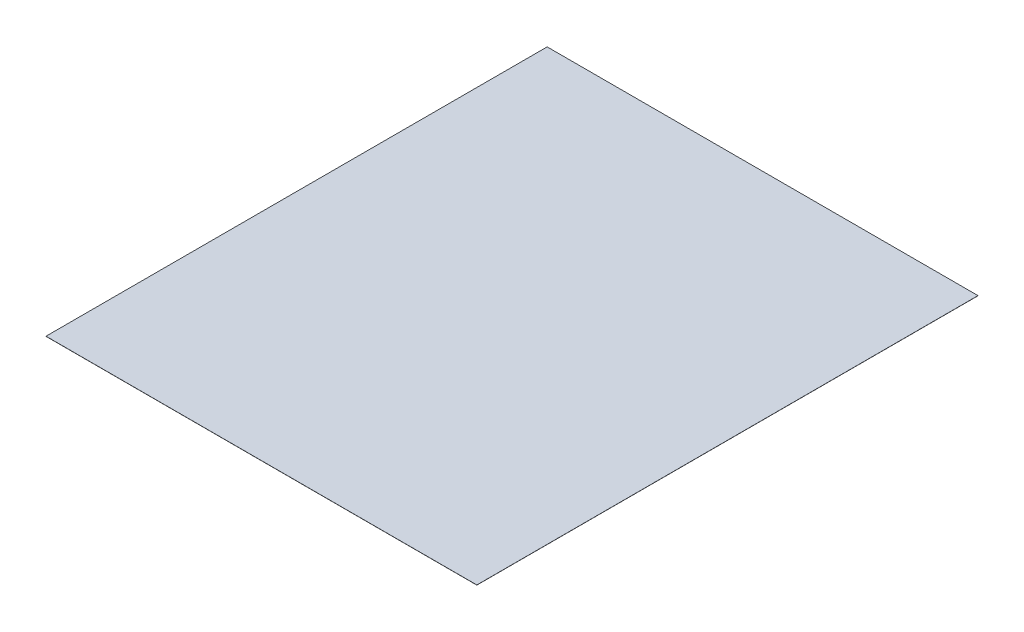
SolidWorks part; units mm, degrees
material "Rubber"
ref_plane "Front Plane" through (0, 0, 0) normal (0, 0, 1) x (1, 0, 0)
ref_plane "Top Plane" through (0, 0, 0) normal (0, 1, 0) x (1, 0, 0)
ref_plane "Right Plane" through (0, 0, 0) normal (1, 0, 0) x (0, 0, -1)
sketch "Sketch1" plane through (0, 0, 0) normal (0, 1, 0) x (1, 0, 0)
  line L1 (0, 0) -> (7315.2, 0)
  line L2 (0, 0) -> (0, 8509)
  line L3 (0, 8509) -> (7315.2, 8509)
  line L4 (7315.2, 0) -> (7315.2, 8509)
  dimension "D1" = 8509
  dimension "D2" = 7315.2
extrude "Boss-Extrude1" add sketch "Sketch1" along normal blind 2.54
